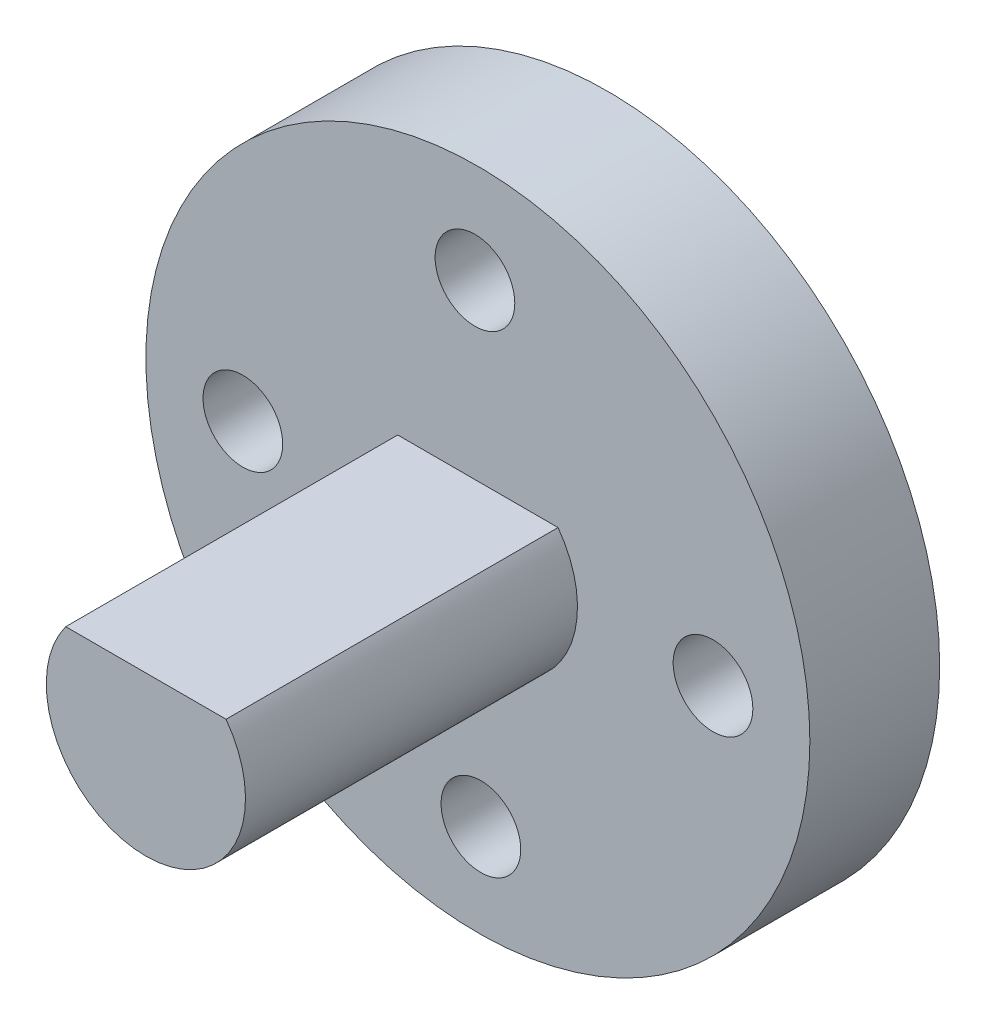
SolidWorks part; units mm, degrees
ref_plane "Plan de face" through (0, 0, 0) normal (0, 0, 1) x (1, 0, 0)
ref_plane "Plan de dessus" through (0, 0, 0) normal (0, 1, 0) x (1, 0, 0)
ref_plane "Plan de droite" through (0, 0, 0) normal (1, 0, 0) x (0, 0, -1)
sketch "Esquisse1" plane through (0, 0, 0) normal (0, 0, 1) x (1, 0, 0)
  circle A0 centre (0, 0) radius 10
  dimension "D1" = 20
extrude "Boss.-Extru.1" add sketch "Esquisse1" along normal blind 3.91
hole_wizard "Dégagement M21" positions "Esquisse3D1" profile "Esquisse3" hole size "M2" standard "Ansi Metric" end condition through all
sketch3d "Esquisse3D1"
  point P0 (-0.0883, 6.9788, 3.91)
  dimension "D1" = 8
sketch "Esquisse3" plane through (-0.0883, 6.9788, 3.91) normal (1, 0, 0) x (0, -1, 0)
  line L0 (0, 0) -> (0, 3.91)
  line L1 (0, 3.91) -> (1.2, 3.91)
  line L2 (1.2, 3.91) -> (1.2, 0)
  line L5 (1.2, 0) -> (0, 0)
  line L11 (0, -6.35) -> (0, 107.95) construction
  dimension "Diamètre du perçage jusqu'au prochain" = 2.4
  dimension "Profondeur du perçage jusqu'au prochain" = 3.91
pattern_circular "Répétition circulaire1" count 4 every 90 about axis through (0.0013, -0.102, 0) along (0, 0, 1) of "Dégagement M21"
sketch "Esquisse4" plane through (0, 0, 3.91) normal (0, 0, 1) x (1, 0, 0)
  circle A0 centre (0, 0) radius 3
  dimension "D1" = 6
extrude "Boss.-Extru.2" add sketch "Esquisse4" along normal blind 10
sketch "Esquisse5" plane through (0, 0, 13.91) normal (0, 0, 1) x (1, 0, 0)
  line L1 (-3, 3) -> (3, 3)
  line L2 (-3, 3) -> (-3, 1.78)
  line L3 (-3, 1.78) -> (3, 1.78)
  line L4 (3, 3) -> (3, 1.78)
  circle A0 centre (0, 0) radius 3 construction
  dimension "D1" = 1.22
extrude "Enlèv. mat.-Extru.1" cut sketch "Esquisse5" against normal up to surface (10 mm away) up to face at (3, 0, 3.91)
sketch "Esquisse6" plane through (0, 0, 0) normal (0, 0, -1) x (-1, 0, 0)
  circle A0 centre (0, 0) radius 4
  dimension "D1" = 8
extrude "Enlèv. mat.-Extru.2" cut sketch "Esquisse6" against normal blind 1.91
